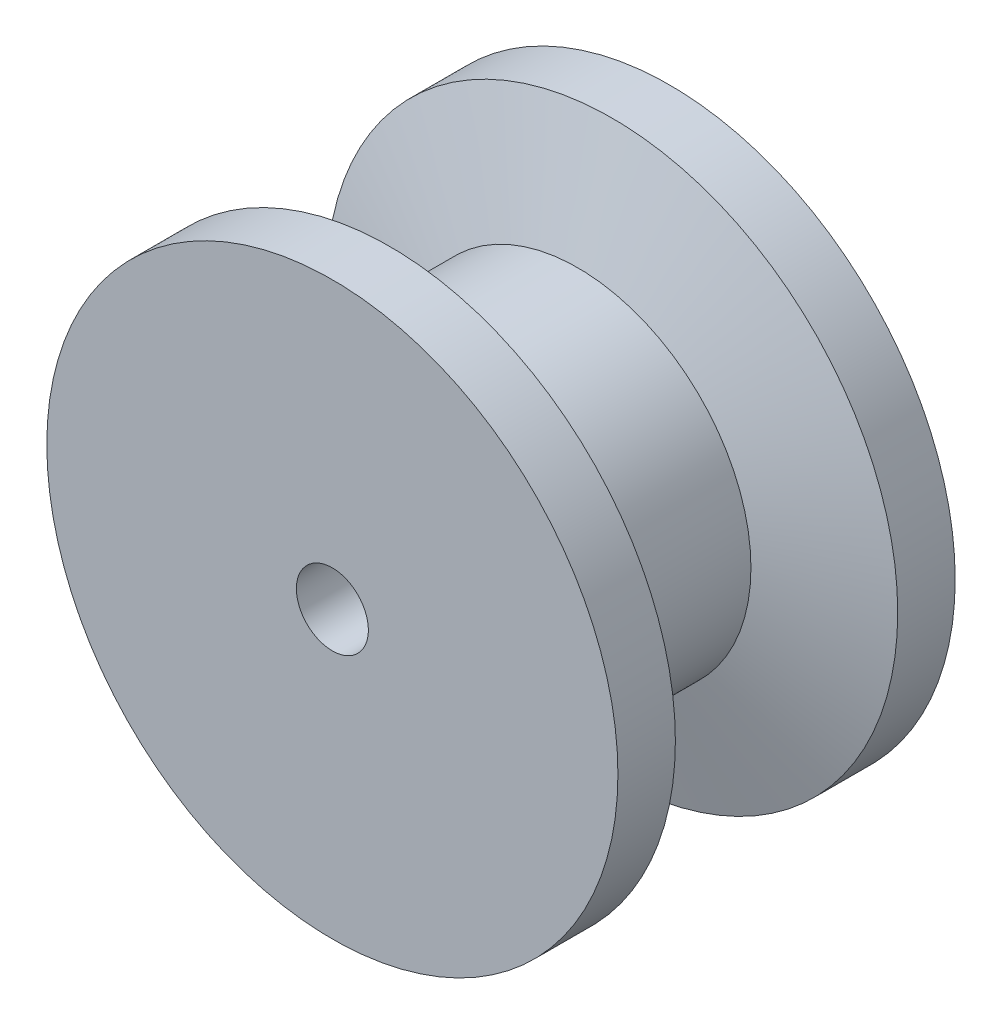
SolidWorks part; units mm, degrees
ref_plane "Front Plane" through (0, 0, 0) normal (0, 0, 1) x (1, 0, 0)
ref_plane "Top Plane" through (0, 0, 0) normal (0, 1, 0) x (1, 0, 0)
ref_plane "Right Plane" through (0, 0, 0) normal (1, 0, 0) x (0, 0, -1)
sketch "Sketch1" plane through (0, 0, 0) normal (1, 0, 0) x (0, 0, -1)
  line L0 (-9.525, 0) -> (9.525, 0) construction
  line L1 (-6.2793, 16.129) -> (6.2793, 16.129) construction
  line L2 (6.2793, 16.129) -> (9.525, 16.129)
  line L5 (-9.525, 16.129) -> (6.2793, 16.129) construction
  line L13 (-6.2793, 16.129) -> (-4.3379, 9.779)
  line L14 (-4.3379, 9.779) -> (4.3379, 9.779)
  line L15 (4.3379, 9.779) -> (6.2793, 16.129)
  line L16 (9.525, 3.175) -> (-9.525, 3.175) construction
  line L17 (0, 16.129) -> (0, 0) construction
  line L18 (-6.2793, 16.129) -> (-9.525, 16.129)
  line L22 (5.3086, 12.954) -> (-5.3086, 12.954) construction
  line L32 (-9.525, 0) -> (-9.525, 16.129)
  line L33 (9.525, 16.129) -> (9.525, 0)
  line L34 (-9.525, 0) -> (9.525, 0)
  point P16 (0, 9.779)
  dimension "D1" = 9.779
  dimension "A" = 34
  dimension "D2" = 3.2457
  dimension "Bore" = 6.35
  dimension "Width" = 19.05
  dimension "W" = 19.05
  dimension "Depth" = 6.35
  dimension "bd" = 10.6172
  dimension "bg" = 12.5586
revolve "Revolve1" add sketch "Sketch1" angle 360 about L0
sketch "Sketch2" plane through (0, 0, -9.525) normal (0, 0, -1) x (-1, 0, 0)
  circle A0 centre (0, 0) radius 3.175
  circle A1 centre (0, 0) radius 12.954 construction
  point P4 (0, 3.175)
sketch "Sketch3" plane through (0, 0, -9.525) normal (0, 0, -1) x (-1, 0, 0)
  circle A0 centre (0, 0) radius 2.032
  dimension "D1" = 4.064
extrude "Cut-Extrude1" cut sketch "Sketch3" against normal through all
